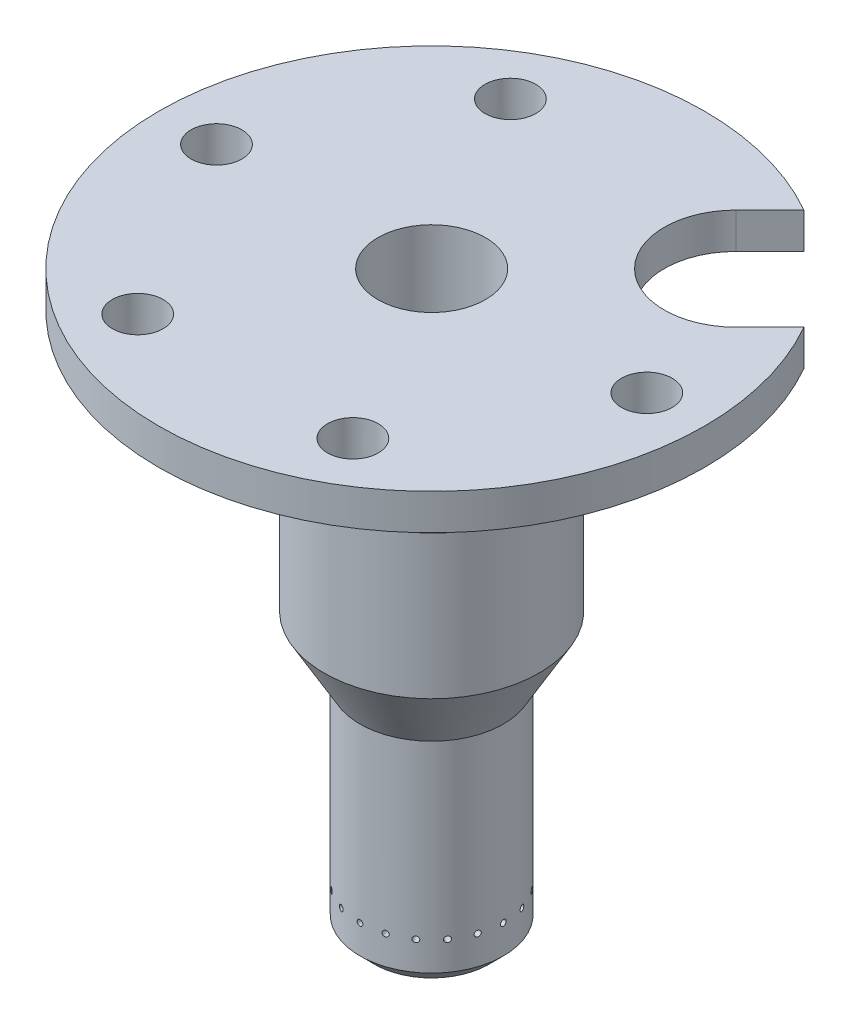
SolidWorks part; units mm, degrees
ref_plane "Front Plane" through (0, 0, 0) normal (0, 0, 1) x (1, 0, 0)
ref_plane "Top Plane" through (0, 0, 0) normal (0, 1, 0) x (1, 0, 0)
ref_plane "Right Plane" through (0, 0, 0) normal (1, 0, 0) x (0, 0, -1)
sketch "Sketch1" plane through (0, 0, 0) normal (0, 0, 1) x (1, 0, 0)
  line L0 (0, 0) -> (0, 66.0706) construction
  line L1 (6.35, 0) -> (6.35, 19.05)
  line L2 (6.35, 0) -> (0, 0)
  line L4 (0, 50.8) -> (0, 0)
  line L5 (6.35, 19.05) -> (9.525, 24.5493)
  line L6 (9.525, 24.5493) -> (9.525, 37.2493)
  line L7 (12.7, 50.8) -> (0, 50.8)
  line L11 (9.525, 37.2493) -> (12.7, 40.4243)
  line L12 (12.7, 40.4243) -> (12.7, 47.625)
  line L14 (12.7, 50.8) -> (24.1554, 50.8)
  line L15 (24.1554, 50.8) -> (24.1554, 47.625)
  line L16 (24.1554, 47.625) -> (12.7, 47.625)
  dimension "D1" = 12.7
  dimension "D2" = 25.4
  dimension "D3" = 19.05
  dimension "D4" = 30
  dimension "D5" = 19.05
  dimension "D6" = 50.8
  dimension "D7" = 48.3108
  dimension "D8" = 45
  dimension "D9" = 12.7
  dimension "D10" = 3.175
revolve "Revolve1" add sketch "Sketch1" angle 360 about L0
chamfer "Chamfer1" distance 1.27 angle 45 1 edges at (0, 0, -6.35)
hole_wizard "#76 (0.02) Diameter Hole1" positions "3DSketch1" profile "Sketch3" hole size "#76" standard "ANSI Inch"
sketch3d "3DSketch1"
  point P0 (6.35, 3.81, 0)
  dimension "D1" = 3.81
sketch "Sketch3" plane through (6.35, 3.81, 0) normal (0, 1, 0) x (0, 0, -1)
  line L0 (0, 0) -> (0, 2.6926)
  line L1 (0, 2.6926) -> (0.254, 2.54)
  line L2 (0.254, 2.54) -> (0.254, 0)
  line L5 (0.254, 0) -> (0, 0)
  line L10 (0, 2.6926) -> (-0.254, 2.54) construction
  line L11 (0, -6.35) -> (0, 107.95) construction
  dimension "Hole Dia." = 0.508
  dimension "Hole Depth" = 2.54
  dimension "Drill Angle" = 118
pattern_circular "CirPattern2" count 20 over 360 about axis through (0, 0, 0) along (0, -1, 0) of "#76 (0.02) Diameter Hole1"
hole_wizard "3/8 (0.375) Diameter Hole2" positions "Sketch6" profile "Sketch7" hole size "3/8" standard "ANSI Inch"
sketch "Sketch6" plane through (0, 50.8, 0) normal (0, 1, 0) x (1, 0, 0)
  point P0 (0, 0)
sketch "Sketch7" plane through (0, 50.8, 0) normal (1, 0, 0) x (0, 0, 1)
  line L0 (0, 0) -> (0, 49.8516)
  line L1 (0, 49.8516) -> (4.7625, 46.99)
  line L2 (4.7625, 46.99) -> (4.7625, 0)
  line L5 (4.7625, 0) -> (0, 0)
  line L10 (0, 49.8516) -> (-4.7625, 46.99) construction
  line L11 (0, -6.35) -> (0, 107.95) construction
  dimension "Hole Dia." = 9.525
  dimension "Hole Depth" = 46.99
  dimension "Drill Angle" = 118
hole_wizard "#8 Clearance Hole1" positions "Sketch8" profile "Sketch9" hole size "#8" standard "ANSI Inch" end condition through all
sketch "Sketch8" plane through (0, 50.8, 0) normal (0, 1, 0) x (1, 0, 0)
  circle A0 centre (0, 0) radius 19.05 construction
  point P0 (19.05, 0)
  dimension "D1" = 38.1
sketch "Sketch9" plane through (19.05, 50.8, 0) normal (1, 0, 0) x (0, 0, 1)
  line L0 (0, 0) -> (0, 50.8)
  line L1 (0, 50.8) -> (2.2479, 50.8)
  line L2 (2.2479, 50.8) -> (2.2479, 0)
  line L5 (2.2479, 0) -> (0, 0)
  line L11 (0, -6.35) -> (0, 107.95) construction
  dimension "Thru Hole Dia." = 4.4958
  dimension "Thru Hole Depth" = 50.8
pattern_circular "CirPattern3" count 6 over 360 about axis through (0, 0, 0) along (0, -1, 0) skipping 1 of "#8 Clearance Hole1"
ref_plane "Plane1" through (0, 0, 0) normal (-1, 0, 0) x (0, 0, -1)
sketch "Sketch11" plane through (0, 0, 0) normal (-1, 0, 0) x (0, 0, -1)
  line L0 (11.6619, -43.2939) -> (12.7889, -43.1953)
  line L1 (12.7889, -43.1953) -> (12.7889, -45.7547)
  line L2 (12.7889, -45.7547) -> (11.6619, -45.6561)
  line L3 (11.43, -45.4031) -> (11.43, -43.5469)
  line L4 (0, 50) -> (0, -50) construction
  arc A0 (11.6619, -45.6561) -> (11.43, -45.4031) centre (11.684, -45.4031) cw
  arc A1 (11.43, -43.5469) -> (11.6619, -43.2939) centre (11.684, -43.5469) cw
revolve "Groove for AS 568-020, O-Ring1" cut sketch "Sketch11"
sketch "Sketch12" plane through (0, 50.8, 0) normal (0, 1, 0) x (1, 0, 0)
  line L0 (11.9896, 20.9698) -> (8.9803, 17.9605)
  line L1 (17.9605, 8.9803) -> (20.9698, 11.9896)
  line L2 (0, 0) -> (17.0804, 17.0804) construction
  line L3 (0, 0) -> (24.1554, 0) construction
  circle A0 centre (0, 0) radius 24.1554 construction
  arc A1 (8.9803, 17.9605) -> (17.9605, 8.9803) centre (13.4704, 13.4704) ccw
  dimension "D1" = 6.35
  dimension "D2" = 19.05
  dimension "D3" = 45
extrude "Cut-Extrude1" cut sketch "Sketch12" against normal blind 3.175 and the other way through all
sketch "Sketch14" plane through (0, 0, 0) normal (0, 0, 1) x (1, 0, 0)
  line L0 (-12.7, 47.625) -> (12.7, 47.625) construction
  line L1 (8.9803, 47.625) -> (17.9605, 47.625) construction
  line L2 (0, 0) -> (0, 55.0424) construction
  circle A0 centre (12.7, 47.625) radius 0.254
  dimension "D1" = 0.508
revolve "relief-cut" cut sketch "Sketch14" angle 360 about L2
